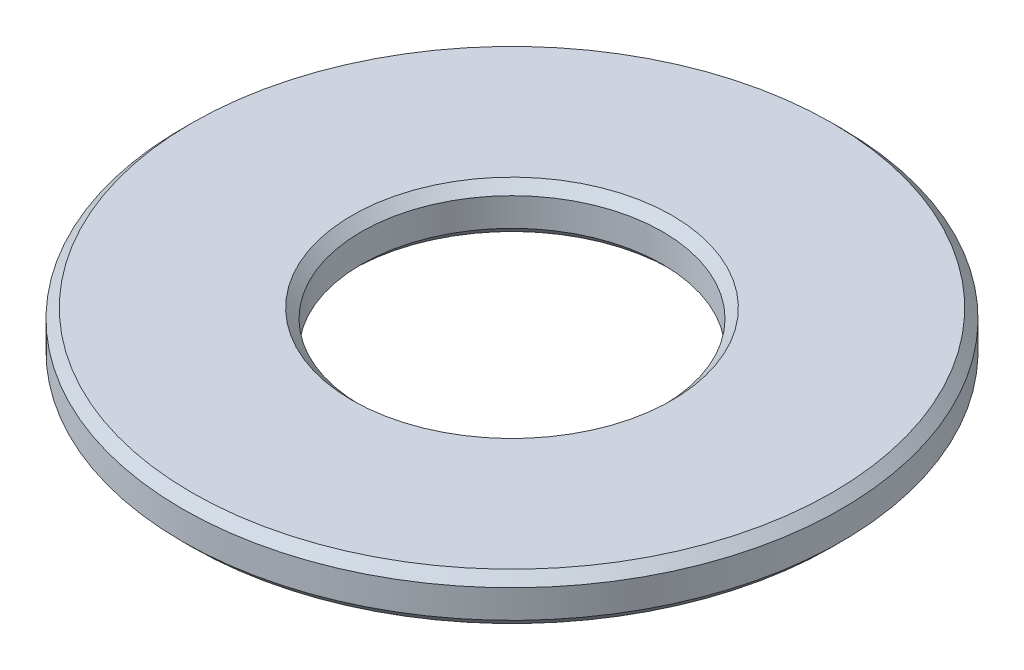
SolidWorks part; units mm, degrees
ref_plane "Front Plane" through (0, 0, 0) normal (0, 0, 1) x (1, 0, 0)
ref_plane "Top Plane" through (0, 0, 0) normal (0, 1, 0) x (1, 0, 0)
ref_plane "Right Plane" through (0, 0, 0) normal (1, 0, 0) x (0, 0, -1)
sketch "Sketch1" plane through (0, 0, 0) normal (0, 1, 0) x (1, 0, 0)
  circle A0 centre (0, 0) radius 1.6
  circle A1 centre (0, 0) radius 3.5
  dimension "D1" = 3.2
  dimension "D2" = 7
extrude "Boss-Extrude1" add sketch "Sketch1" along normal blind 0.5
chamfer "Chamfer1" distance 0.1 angle 45 4 edges at (0, 0, 1.6) (0, 0, 3.5) (0, 0.5, 3.5) (0, 0.5, 1.6)
